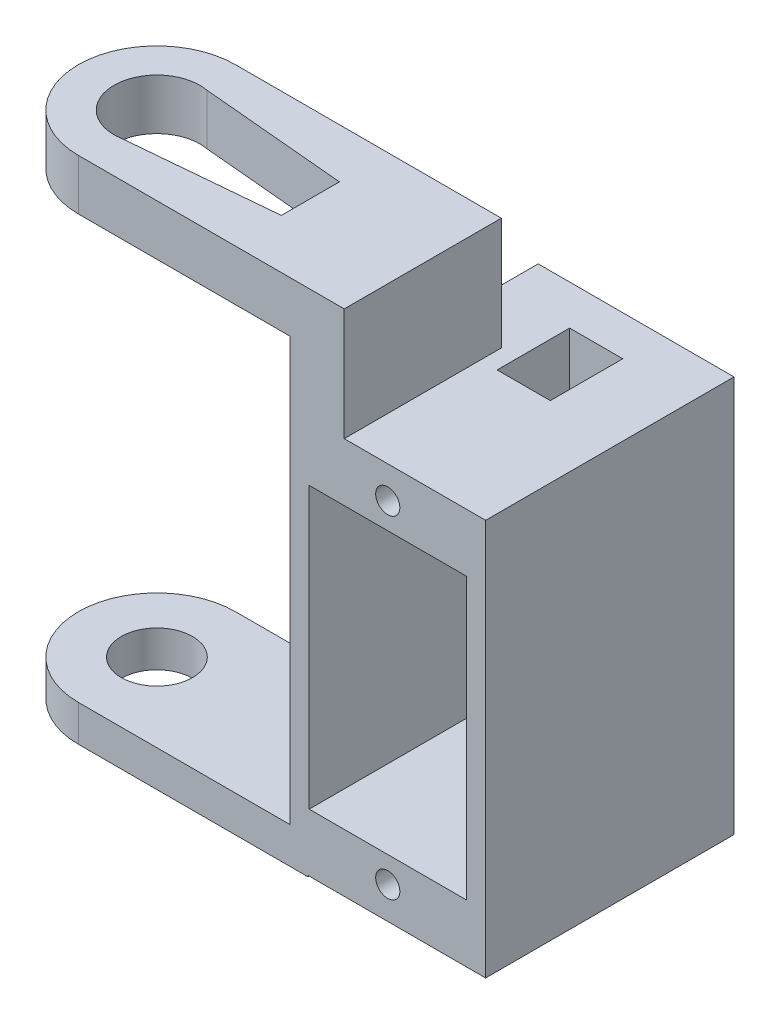
SolidWorks part; units mm, degrees
material "ABS"
ref_plane "Front Plane" through (0, 0, 0) normal (0, 0, 1) x (1, 0, 0)
ref_plane "Top Plane" through (0, 0, 0) normal (0, 1, 0) x (1, 0, 0)
ref_plane "Right Plane" through (0, 0, 0) normal (1, 0, 0) x (0, 0, -1)
sketch "Sketch1" plane through (0, 0, 0) normal (0, 0, 1) x (1, 0, 0)
  line L1 (-67.5, 42.6) -> (-51.3, 42.6)
  line L2 (-67.5, 42.6) -> (-67.5, 75.4)
  line L3 (-67.5, 75.4) -> (-51.3, 75.4)
  line L4 (-51.3, 42.6) -> (-51.3, 75.4)
extrude "Boss-Extrude1" add sketch "Sketch1" along normal mid plane 20.55 from offset 3.775
sketch "Sketch2" plane through (0, 0, 0) normal (1, 0, 0) x (0, 0, -1)
  line L0 (-6.5, 42.6) -> (-6.5, 75.4) construction
  line L1 (-6.5, 73) -> (6.5, 73)
  line L2 (-6.5, 73) -> (-6.5, 84.7)
  line L3 (-6.5, 84.7) -> (6.5, 84.7)
  line L4 (6.5, 73) -> (6.5, 84.7)
extrude "Boss-Extrude2" add sketch "Sketch2" along normal mid plane 4.5 from offset 65.25
sketch "Sketch3" plane through (0, 0, 0) normal (0, 1, 0) x (1, 0, 0)
  circle A0 centre (-85, 0) radius 6.5
extrude "Boss-Extrude3" add sketch "Sketch3" along normal mid plane 4.2 from offset 82.6
sketch "Sketch4" plane through (0, 0, 0) normal (0, 1, 0) x (1, 0, 0)
  line L0 (-63, 6.5) -> (-67.5, 6.5) construction
  line L1 (-85, -6.5) -> (-66, -6.5)
  line L2 (-85, -6.5) -> (-85, 6.5)
  line L3 (-85, 6.5) -> (-66, 6.5)
  line L4 (-66, -6.5) -> (-66, 6.5)
  circle A0 centre (-85, 0) radius 6.5 construction
extrude "Boss-Extrude4" add sketch "Sketch4" along normal mid plane 4.2 from offset 82.6
sketch "Sketch5" plane through (0, 0, 0) normal (0, 1, 0) x (1, 0, 0)
  circle A0 centre (-85, 0) radius 3.55
extrude "Cut-Extrude1" cut sketch "Sketch5" against normal mid plane 4.2 from offset 82.6
sketch "Sketch6" plane through (0, 0, 0) normal (0, 1, 0) x (1, 0, 0)
  line L0 (-85, -3.55) -> (-72.3, -2.4033)
  line L1 (-72.3, -2.4033) -> (-72.3, 2.4033)
  line L2 (-72.3, 2.4033) -> (-85, 3.55)
  line L3 (-85, 3.55) -> (-85, -3.55)
  circle A0 centre (-85, 0) radius 3.55 construction
extrude "Cut-Extrude2" cut sketch "Sketch6" against normal mid plane 4.2 from offset 82.6
sketch "Sketch7" plane through (0, 0, 0) normal (0, 1, 0) x (1, 0, 0)
  circle A0 centre (-85, 0) radius 6.5
extrude "Boss-Extrude5" add sketch "Sketch7" along normal mid plane 3 from offset 44
sketch "Sketch8" plane through (0, 0, 0) normal (0, 1, 0) x (1, 0, 0)
  line L0 (-63, 6.5) -> (-67.5, 6.5) construction
  line L1 (-85, -6.5) -> (-66, -6.5)
  line L2 (-85, -6.5) -> (-85, 6.5)
  line L3 (-85, 6.5) -> (-66, 6.5)
  line L4 (-66, -6.5) -> (-66, 6.5)
extrude "Boss-Extrude6" add sketch "Sketch8" along normal mid plane 3 from offset 44
sketch "Sketch9" plane through (0, 0, 0) normal (0, 1, 0) x (1, 0, 0)
  circle A0 centre (-85, 0) radius 2.95
extrude "Cut-Extrude3" cut sketch "Sketch9" against normal mid plane 3 from offset 44
sketch "Sketch10" plane through (0, 0, 0) normal (0, 0, 1) x (1, 0, 0)
  line L1 (-65.9, 47.4) -> (-52.9, 47.4)
  line L2 (-65.9, 47.4) -> (-65.9, 70.6)
  line L3 (-65.9, 70.6) -> (-52.9, 70.6)
  line L4 (-52.9, 47.4) -> (-52.9, 70.6)
extrude "Cut-Extrude4" cut sketch "Sketch10" against normal mid plane 17.25 from offset 2.125
sketch "Sketch11" plane through (0, 0, 0) normal (0, 0, 1) x (1, 0, 0)
  circle A0 centre (-59.4, 45.25) radius 1
extrude "Cut-Extrude5" cut sketch "Sketch11" against normal mid plane 6 from offset 3.5
sketch "Sketch12" plane through (0, 0, 0) normal (0, 0, 1) x (1, 0, 0)
  circle A0 centre (-59.4, 72.75) radius 1
extrude "Cut-Extrude6" cut sketch "Sketch12" against normal mid plane 6 from offset 3.5
sketch "Sketch13" plane through (0, 0, 0) normal (0, 0, 1) x (1, 0, 0)
  circle A0 centre (-59.4, 64.5) radius 3.15
extrude "Cut-Extrude7" cut sketch "Sketch13" against normal mid plane 2.6 from offset 12.75
sketch "Sketch14" plane through (0, 0, 0) normal (0, 1, 0) x (1, 0, 0)
  line L1 (-61.6, 4.75) -> (-57.2, 4.75)
  line L2 (-61.6, 4.75) -> (-61.6, 10.75)
  line L3 (-61.6, 10.75) -> (-57.2, 10.75)
  line L4 (-57.2, 4.75) -> (-57.2, 10.75)
extrude "Cut-Extrude8" cut sketch "Sketch14" against normal mid plane 4.8 from offset 73
